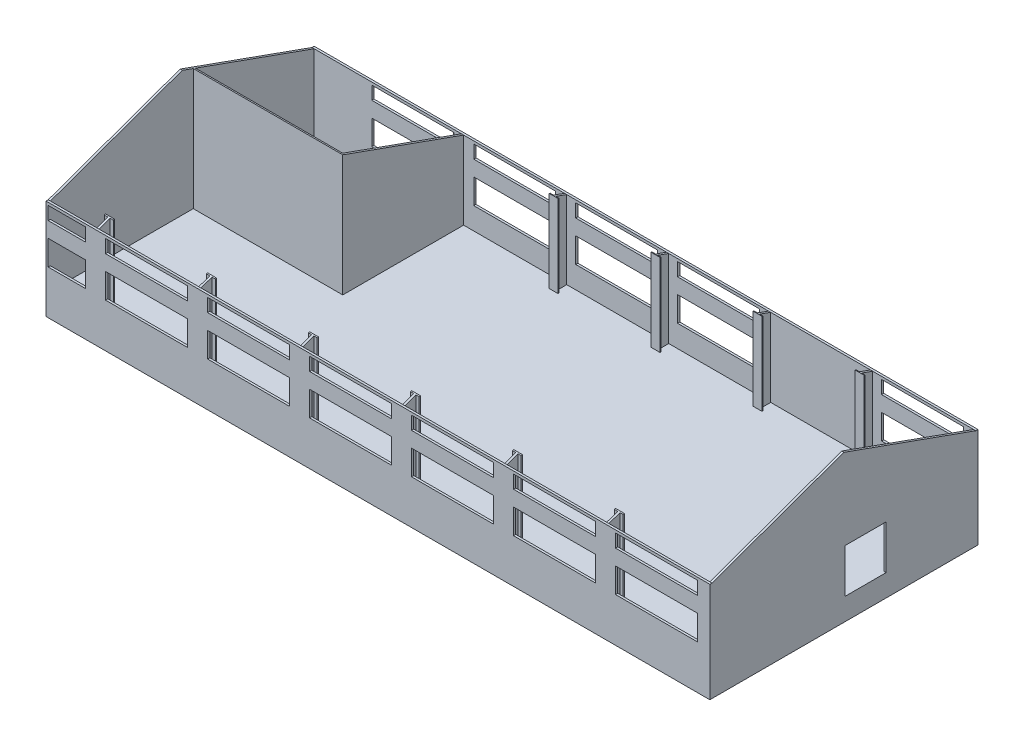
SolidWorks part; units mm, degrees
ref_plane "正面" through (0, 0, 0) normal (0, 0, 1) x (1, 0, 0)
ref_plane "平面" through (0, 0, 0) normal (0, 1, 0) x (1, 0, 0)
ref_plane "右側面" through (0, 0, 0) normal (1, 0, 0) x (0, 0, -1)
sketch "ｽｹｯﾁ3" plane through (0, 0, 0) normal (0, 1, 0) x (1, 0, 0)
  line L1 (-95.6421, 11968.1626) -> (29904.3579, 11968.1626)
  line L2 (-95.6421, 11968.1626) -> (-95.6421, -31.8374)
  line L3 (-95.6421, -31.8374) -> (29904.3579, -31.8374)
  line L4 (29904.3579, 11968.1626) -> (29904.3579, -31.8374)
  dimension "D1" = 30000
  dimension "D2" = 12000
extrude "ﾎﾞｽ - 押し出し2" add sketch "ｽｹｯﾁ3" along normal blind 1000
sketch "ｽｹｯﾁ4" plane through (29904.3579, 0, 0) normal (1, 0, 0) x (0, 0, -1)
  line L0 (-31.8374, 0) -> (-31.8374, 4550)
  line L1 (-31.8374, 4550) -> (5968.1626, 6700)
  line L2 (5968.1626, 6700) -> (11968.1626, 4550)
  line L3 (11968.1626, 4550) -> (11968.1626, 0)
  line L4 (11968.1626, 0) -> (-31.8374, 0)
  dimension "D1" = 12000
  dimension "D2" = 12000
  dimension "D3" = 6000
  dimension "D4" = 4550
  dimension "D5" = 4550
  dimension "D6" = 6700
extrude "ﾎﾞｽ - 押し出し3" add sketch "ｽｹｯﾁ4" along normal blind 100
sketch "ｽｹｯﾁ7" plane through (-95.6421, 0, 0) normal (-1, 0, 0) x (0, 0, 1)
  line L0 (-11968.1626, 0) -> (-11968.1626, 4550)
  line L1 (-11968.1626, 4550) -> (-5968.1626, 6700)
  line L2 (-5968.1626, 6700) -> (31.8374, 4550)
  line L3 (31.8374, 4550) -> (31.8374, 0)
  line L4 (31.8374, 0) -> (-11968.1626, 0)
  dimension "D1" = 6700
  dimension "D2" = 4550
  dimension "D3" = 4550
  dimension "D4" = 6000
  dimension "D5" = 12000
extrude "ﾎﾞｽ - 押し出し4" add sketch "ｽｹｯﾁ7" along normal blind 100
sketch "ｽｹｯﾁ8" plane through (0, 0, -11968.1626) normal (0, 0, -1) x (-1, 0, 0)
  line L1 (-30004.3579, 0) -> (195.6421, 0)
  line L2 (-30004.3579, 0) -> (-30004.3579, 4550)
  line L3 (-30004.3579, 4550) -> (195.6421, 4550)
  line L4 (195.6421, 0) -> (195.6421, 4550)
extrude "ﾎﾞｽ - 押し出し5" add sketch "ｽｹｯﾁ8" along normal blind 100
sketch "ｽｹｯﾁ9" plane through (0, 0, 31.8374) normal (0, 0, 1) x (1, 0, 0)
  line L1 (-195.6421, 0) -> (30004.3579, 0)
  line L2 (-195.6421, 0) -> (-195.6421, 4550)
  line L3 (-195.6421, 4550) -> (30004.3579, 4550)
  line L4 (30004.3579, 0) -> (30004.3579, 4550)
extrude "ﾎﾞｽ - 押し出し7" add sketch "ｽｹｯﾁ9" along normal blind 100
sketch "ｽｹｯﾁ10" plane through (0, 1000, 0) normal (0, 1, 0) x (1, 0, 0)
  line L0 (-95.6421, 6568.1626) -> (6604.3579, 6568.1626)
  line L1 (-95.6421, 11968.1626) -> (-95.6421, -31.8374) construction
  line L2 (6604.3579, 6568.1626) -> (6604.3579, 11968.1626)
  line L3 (29904.3579, 11968.1626) -> (-95.6421, 11968.1626) construction
  line L4 (6604.3579, 11968.1626) -> (6704.3579, 11968.1626)
  line L5 (6704.3579, 11968.1626) -> (6704.3579, 6468.1626)
  line L6 (6704.3579, 6468.1626) -> (-95.6421, 6468.1626)
  line L7 (-95.6421, 6468.1626) -> (-95.6421, 6568.1626)
  dimension "D1" = 5500
  dimension "D2" = 6800
  dimension "D3" = 100
  dimension "D4" = 100
extrude "ﾎﾞｽ - 押し出し8" add sketch "ｽｹｯﾁ10" along normal blind 5700
sketch "ｽｹｯﾁ13" plane through (29904.3579, 0, 0) normal (-1, 0, 0) x (0, 0, 1)
  line L0 (31.8374, 1000) -> (-11968.1626, 1000) construction
  line L1 (-7888.1626, 1000) -> (-6008.1626, 1000)
  line L2 (-7888.1626, 1000) -> (-7888.1626, 3000)
  line L3 (-7888.1626, 3000) -> (-6008.1626, 3000)
  line L4 (-6008.1626, 1000) -> (-6008.1626, 3000)
  dimension "D1" = 1880
  dimension "D2" = 2000
  dimension "D3" = 40
extrude "ｶｯﾄ - 押し出し3" cut sketch "ｽｹｯﾁ13" against normal blind 100
sketch "ｽｹｯﾁ14" plane through (0, 1000, 0) normal (0, 1, 0) x (1, 0, 0)
  line L0 (25314.3579, 11968.1626) -> (25314.3579, 11468.1626)
  line L1 (29904.3579, 11968.1626) -> (6704.3579, 11968.1626) construction
  line L2 (25314.3579, 11468.1626) -> (25464.3579, 11468.1626)
  line L3 (25464.3579, 11468.1626) -> (25464.3579, 11418.1626)
  line L4 (25464.3579, 11418.1626) -> (25064.3579, 11418.1626)
  line L5 (25064.3579, 11418.1626) -> (25064.3579, 11468.1626)
  line L6 (25064.3579, 11468.1626) -> (25214.3579, 11468.1626)
  line L7 (25214.3579, 11468.1626) -> (25214.3579, 11968.1626)
  line L8 (-95.6421, 11968.1626) -> (6604.3579, 11968.1626) construction
  line L9 (25214.3579, 11968.1626) -> (25314.3579, 11968.1626)
  line L10 (25264.3579, 12167.4241) -> (25264.3579, 11163.5533) construction
  line L11 (29904.3579, 11968.1626) -> (29904.3579, 5968.1626) construction
  line L12 (20674.3579, 11968.1626) -> (20674.3579, 11468.1626)
  line L13 (20674.3579, 11468.1626) -> (20824.3579, 11468.1626)
  line L14 (20824.3579, 11468.1626) -> (20824.3579, 11418.1626)
  line L15 (20824.3579, 11418.1626) -> (20424.3579, 11418.1626)
  line L16 (20424.3579, 11418.1626) -> (20424.3579, 11468.1626)
  line L17 (20424.3579, 11468.1626) -> (20574.3579, 11468.1626)
  line L18 (20574.3579, 11468.1626) -> (20574.3579, 11968.1626)
  line L19 (20574.3579, 11968.1626) -> (20674.3579, 11968.1626)
  line L20 (20624.3579, 12167.4241) -> (20624.3579, 11163.5533) construction
  line L21 (16034.3579, 11968.1626) -> (16034.3579, 11468.1626)
  line L22 (16034.3579, 11468.1626) -> (16184.3579, 11468.1626)
  line L23 (16184.3579, 11468.1626) -> (16184.3579, 11418.1626)
  line L24 (16184.3579, 11418.1626) -> (15784.3579, 11418.1626)
  line L25 (15784.3579, 11418.1626) -> (15784.3579, 11468.1626)
  line L26 (15784.3579, 11468.1626) -> (15934.3579, 11468.1626)
  line L27 (15934.3579, 11468.1626) -> (15934.3579, 11968.1626)
  line L28 (15934.3579, 11968.1626) -> (16034.3579, 11968.1626)
  line L29 (15984.3579, 12167.4241) -> (15984.3579, 11163.5533) construction
  line L30 (11394.3579, 11968.1626) -> (11394.3579, 11468.1626)
  line L31 (11394.3579, 11468.1626) -> (11544.3579, 11468.1626)
  line L32 (11544.3579, 11468.1626) -> (11544.3579, 11418.1626)
  line L33 (11544.3579, 11418.1626) -> (11144.3579, 11418.1626)
  line L34 (11144.3579, 11418.1626) -> (11144.3579, 11468.1626)
  line L35 (11144.3579, 11468.1626) -> (11294.3579, 11468.1626)
  line L36 (11294.3579, 11468.1626) -> (11294.3579, 11968.1626)
  line L37 (11294.3579, 11968.1626) -> (11394.3579, 11968.1626)
  line L38 (11344.3579, 12167.4241) -> (11344.3579, 11163.5533) construction
  line L39 (2014.3579, -31.8374) -> (2014.3579, 468.1626)
  line L40 (25214.3579, -31.8374) -> (25214.3579, 468.1626)
  line L41 (2014.3579, 468.1626) -> (1864.3579, 468.1626)
  line L42 (25214.3579, 468.1626) -> (25064.3579, 468.1626)
  line L43 (25064.3579, 468.1626) -> (25064.3579, 518.1626)
  line L44 (25064.3579, 518.1626) -> (25464.3579, 518.1626)
  line L45 (25464.3579, 518.1626) -> (25464.3579, 468.1626)
  line L46 (25464.3579, 468.1626) -> (25314.3579, 468.1626)
  line L47 (25314.3579, 468.1626) -> (25314.3579, -31.8374)
  line L48 (-95.6421, -31.8374) -> (29904.3579, -31.8374) construction
  line L49 (25314.3579, -31.8374) -> (25214.3579, -31.8374)
  line L50 (25264.3579, 648.8294) -> (25264.3579, -317.6522) construction
  line L51 (1864.3579, 468.1626) -> (1864.3579, 518.1626)
  line L52 (1864.3579, 518.1626) -> (2264.3579, 518.1626)
  line L53 (2264.3579, 518.1626) -> (2264.3579, 468.1626)
  line L54 (29904.3579, 5968.1626) -> (29904.3579, -31.8374) construction
  line L55 (20574.3579, -31.8374) -> (20574.3579, 468.1626)
  line L56 (20574.3579, 468.1626) -> (20424.3579, 468.1626)
  line L57 (20424.3579, 468.1626) -> (20424.3579, 518.1626)
  line L58 (20424.3579, 518.1626) -> (20824.3579, 518.1626)
  line L59 (20824.3579, 518.1626) -> (20824.3579, 468.1626)
  line L60 (20824.3579, 468.1626) -> (20674.3579, 468.1626)
  line L61 (20674.3579, 468.1626) -> (20674.3579, -31.8374)
  line L62 (20674.3579, -31.8374) -> (20574.3579, -31.8374)
  line L63 (20624.3579, 648.8294) -> (20624.3579, -317.6522) construction
  line L64 (15934.3579, -31.8374) -> (15934.3579, 468.1626)
  line L65 (15934.3579, 468.1626) -> (15784.3579, 468.1626)
  line L66 (15784.3579, 468.1626) -> (15784.3579, 518.1626)
  line L67 (15784.3579, 518.1626) -> (16184.3579, 518.1626)
  line L68 (16184.3579, 518.1626) -> (16184.3579, 468.1626)
  line L69 (16184.3579, 468.1626) -> (16034.3579, 468.1626)
  line L70 (16034.3579, 468.1626) -> (16034.3579, -31.8374)
  line L71 (16034.3579, -31.8374) -> (15934.3579, -31.8374)
  line L72 (15984.3579, 648.8294) -> (15984.3579, -317.6522) construction
  line L73 (11294.3579, -31.8374) -> (11294.3579, 468.1626)
  line L74 (11294.3579, 468.1626) -> (11144.3579, 468.1626)
  line L75 (11144.3579, 468.1626) -> (11144.3579, 518.1626)
  line L76 (11144.3579, 518.1626) -> (11544.3579, 518.1626)
  line L77 (11544.3579, 518.1626) -> (11544.3579, 468.1626)
  line L78 (11544.3579, 468.1626) -> (11394.3579, 468.1626)
  line L79 (11394.3579, 468.1626) -> (11394.3579, -31.8374)
  line L80 (11394.3579, -31.8374) -> (11294.3579, -31.8374)
  line L81 (11344.3579, 648.8294) -> (11344.3579, -317.6522) construction
  line L82 (6654.3579, -31.8374) -> (6654.3579, 468.1626)
  line L83 (6654.3579, 468.1626) -> (6504.3579, 468.1626)
  line L84 (6504.3579, 468.1626) -> (6504.3579, 518.1626)
  line L85 (6504.3579, 518.1626) -> (6904.3579, 518.1626)
  line L86 (6904.3579, 518.1626) -> (6904.3579, 468.1626)
  line L87 (6904.3579, 468.1626) -> (6754.3579, 468.1626)
  line L88 (6754.3579, 468.1626) -> (6754.3579, -31.8374)
  line L89 (6754.3579, -31.8374) -> (6654.3579, -31.8374)
  line L90 (6704.3579, 648.8294) -> (6704.3579, -317.6522) construction
  line L91 (29904.3579, -31.8374) -> (-95.6421, -31.8374) construction
  line L92 (2264.3579, 468.1626) -> (2114.3579, 468.1626)
  line L93 (2114.3579, 468.1626) -> (2114.3579, -31.8374)
  line L94 (2114.3579, -31.8374) -> (2014.3579, -31.8374)
  line L95 (2064.3579, 648.8294) -> (2064.3579, -317.6522) construction
  dimension "D1" = 100
  dimension "D2" = 50
  dimension "D3" = 400
  dimension "D4" = 150
  dimension "D5" = 50
  dimension "D6" = 4640
  dimension "D7" = 500
  dimension "D8" = 100
  dimension "D9" = 50
  dimension "D10" = 400
  dimension "D11" = 150
  dimension "D12" = 50
  dimension "D13" = 500
  dimension "D14" = 100
  dimension "D15" = 50
  dimension "D16" = 400
  dimension "D17" = 150
  dimension "D18" = 50
  dimension "D19" = 500
  dimension "D20" = 100
  dimension "D21" = 50
  dimension "D22" = 400
  dimension "D23" = 150
  dimension "D24" = 50
  dimension "D25" = 500
  dimension "D26" = 4640
  dimension "D27" = 4640
  dimension "D28" = 4640
  dimension "D29" = 100
  dimension "D30" = 50
  dimension "D31" = 400
  dimension "D32" = 150
  dimension "D33" = 500
  dimension "D34" = 50
  dimension "D35" = 4640
  dimension "D36" = 100
  dimension "D37" = 50
  dimension "D38" = 400
  dimension "D39" = 150
  dimension "D40" = 50
  dimension "D41" = 100
  dimension "D42" = 50
  dimension "D43" = 400
  dimension "D44" = 150
  dimension "D45" = 50
  dimension "D46" = 100
  dimension "D47" = 50
  dimension "D48" = 400
  dimension "D49" = 150
  dimension "D50" = 50
  dimension "D51" = 100
  dimension "D52" = 50
  dimension "D53" = 400
  dimension "D54" = 150
  dimension "D55" = 50
  dimension "D56" = 500
  dimension "D57" = 500
  dimension "D58" = 500
  dimension "D59" = 500
  dimension "D60" = 4640
  dimension "D61" = 4640
  dimension "D62" = 4640
  dimension "D63" = 4640
  dimension "D64" = 100
  dimension "D65" = 50
  dimension "D66" = 400
  dimension "D67" = 50
  dimension "D68" = 500
  dimension "D69" = 4640
  dimension "D70" = 150
extrude "ﾎﾞｽ - 押し出し9" add sketch "ｽｹｯﾁ14" along normal blind 4000
sketch "ｽｹｯﾁ15" plane through (0, 0, -11968.1626) normal (0, 0, 1) x (1, 0, 0)
  line L0 (29904.3579, 1000) -> (25314.3579, 1000) construction
  line L1 (25714.3579, 3130) -> (29444.3579, 3130)
  line L2 (25714.3579, 3130) -> (25714.3579, 2000)
  line L3 (25714.3579, 2000) -> (29444.3579, 2000)
  line L4 (29444.3579, 3130) -> (29444.3579, 2000)
  line L5 (25714.3579, 4430) -> (29444.3579, 4430)
  line L6 (25714.3579, 4430) -> (25714.3579, 3830)
  line L7 (25714.3579, 3830) -> (29444.3579, 3830)
  line L8 (29444.3579, 4430) -> (29444.3579, 3830)
  line L9 (25314.3579, 4550) -> (25314.3579, 1000) construction
  line L10 (11294.3579, 4550) -> (11294.3579, 1000) construction
  line L11 (11294.3579, 1000) -> (6704.3579, 1000) construction
  line L18 (16439.3579, 3130) -> (20169.3579, 3130)
  line L19 (16439.3579, 2000) -> (20169.3579, 2000)
  line L20 (20169.3579, 3130) -> (20169.3579, 2000)
  line L21 (16439.3579, 3130) -> (16439.3579, 2000)
  line L22 (16439.3579, 4430) -> (16439.3579, 3830)
  line L23 (16439.3579, 3830) -> (20169.3579, 3830)
  line L24 (16439.3579, 4430) -> (20169.3579, 4430)
  line L25 (20169.3579, 4430) -> (20169.3579, 3830)
  line L26 (11801.8579, 3130) -> (15531.8579, 3130)
  line L27 (11801.8579, 2000) -> (15531.8579, 2000)
  line L28 (15531.8579, 3130) -> (15531.8579, 2000)
  line L29 (11801.8579, 3130) -> (11801.8579, 2000)
  line L30 (11801.8579, 4430) -> (11801.8579, 3830)
  line L31 (11801.8579, 3830) -> (15531.8579, 3830)
  line L32 (11801.8579, 4430) -> (15531.8579, 4430)
  line L33 (15531.8579, 4430) -> (15531.8579, 3830)
  line L34 (7164.3579, 3130) -> (10894.3579, 3130)
  line L35 (7164.3579, 2000) -> (10894.3579, 2000)
  line L36 (10894.3579, 3130) -> (10894.3579, 2000)
  line L37 (7164.3579, 3130) -> (7164.3579, 2000)
  line L38 (7164.3579, 4430) -> (7164.3579, 3830)
  line L39 (7164.3579, 3830) -> (10894.3579, 3830)
  line L40 (7164.3579, 4430) -> (10894.3579, 4430)
  line L41 (10894.3579, 4430) -> (10894.3579, 3830)
  line L42 (21076.8579, 3130) -> (24806.8579, 3130) [skipped]
  line L43 (21076.8579, 2000) -> (24806.8579, 2000) [skipped]
  line L44 (24806.8579, 3130) -> (24806.8579, 2000) [skipped]
  line L45 (21076.8579, 3130) -> (21076.8579, 2000) [skipped]
  line L46 (21076.8579, 4430) -> (21076.8579, 3830) [skipped]
  line L47 (21076.8579, 3830) -> (24806.8579, 3830) [skipped]
  line L48 (21076.8579, 4430) -> (24806.8579, 4430) [skipped]
  line L49 (24806.8579, 4430) -> (24806.8579, 3830) [skipped]
  line L52 (6254.3579, 3130) -> (6254.3579, 2000)
  line L53 (2524.3579, 3130) -> (2524.3579, 2000)
  line L54 (2524.3579, 2000) -> (6254.3579, 2000)
  line L55 (2524.3579, 3130) -> (6254.3579, 3130)
  line L56 (2524.3579, 3830) -> (6254.3579, 3830)
  line L57 (2524.3579, 4430) -> (2524.3579, 3830)
  line L58 (2524.3579, 4430) -> (6254.3579, 4430)
  line L59 (6254.3579, 4430) -> (6254.3579, 3830)
  dimension "D1" = 1000
  dimension "D2" = 3730
  dimension "D3" = 400
  dimension "D4" = 700
  dimension "D5" = 3730
  dimension "D6" = 400
  dimension "D7" = 1130
  dimension "D8" = 600
  dimension "D10" = 3730
  dimension "D11" = 400
  dimension "D12" = 1000
  dimension "D9" = 5
extrude "ｶｯﾄ - 押し出し4" cut sketch "ｽｹｯﾁ15" against normal blind 100
sketch "ｽｹｯﾁ16" plane through (0, 0, 31.8374) normal (0, 0, -1) x (-1, 0, 0)
  line L0 (-25314.3579, 1000) -> (-29904.3579, 1000) construction
  line L1 (-29444.3579, 3130) -> (-25714.3579, 3130)
  line L2 (-29444.3579, 3130) -> (-29444.3579, 2000)
  line L3 (-29444.3579, 2000) -> (-25714.3579, 2000)
  line L4 (-25714.3579, 3130) -> (-25714.3579, 2000)
  line L5 (-29444.3579, 4430) -> (-25714.3579, 4430)
  line L6 (-29444.3579, 4430) -> (-29444.3579, 3830)
  line L7 (-29444.3579, 3830) -> (-25714.3579, 3830)
  line L8 (-25714.3579, 4430) -> (-25714.3579, 3830)
  line L9 (-25314.3579, 4550) -> (-25314.3579, 1000) construction
  line L10 (-24804.3579, 3130) -> (-21074.3579, 3130)
  line L11 (-24804.3579, 2000) -> (-21074.3579, 2000)
  line L12 (-24804.3579, 3130) -> (-24804.3579, 2000)
  line L13 (-21074.3579, 3130) -> (-21074.3579, 2000)
  line L14 (-24804.3579, 3830) -> (-21074.3579, 3830)
  line L15 (-24804.3579, 4430) -> (-24804.3579, 3830)
  line L16 (-24804.3579, 4430) -> (-21074.3579, 4430)
  line L17 (-21074.3579, 4430) -> (-21074.3579, 3830)
  line L18 (-20164.3579, 3130) -> (-16434.3579, 3130)
  line L19 (-20164.3579, 2000) -> (-16434.3579, 2000)
  line L20 (-20164.3579, 3130) -> (-20164.3579, 2000)
  line L21 (-16434.3579, 3130) -> (-16434.3579, 2000)
  line L22 (-20164.3579, 3830) -> (-16434.3579, 3830)
  line L23 (-20164.3579, 4430) -> (-20164.3579, 3830)
  line L24 (-20164.3579, 4430) -> (-16434.3579, 4430)
  line L25 (-16434.3579, 4430) -> (-16434.3579, 3830)
  line L26 (-15524.3579, 3130) -> (-11794.3579, 3130)
  line L27 (-15524.3579, 2000) -> (-11794.3579, 2000)
  line L28 (-15524.3579, 3130) -> (-15524.3579, 2000)
  line L29 (-11794.3579, 3130) -> (-11794.3579, 2000)
  line L30 (-15524.3579, 3830) -> (-11794.3579, 3830)
  line L31 (-15524.3579, 4430) -> (-15524.3579, 3830)
  line L32 (-15524.3579, 4430) -> (-11794.3579, 4430)
  line L33 (-11794.3579, 4430) -> (-11794.3579, 3830)
  line L34 (-10884.3579, 3130) -> (-7154.3579, 3130)
  line L35 (-10884.3579, 2000) -> (-7154.3579, 2000)
  line L36 (-10884.3579, 3130) -> (-10884.3579, 2000)
  line L37 (-7154.3579, 3130) -> (-7154.3579, 2000)
  line L38 (-10884.3579, 3830) -> (-7154.3579, 3830)
  line L39 (-10884.3579, 4430) -> (-10884.3579, 3830)
  line L40 (-10884.3579, 4430) -> (-7154.3579, 4430)
  line L41 (-7154.3579, 4430) -> (-7154.3579, 3830)
  line L42 (-6244.3579, 3130) -> (-2514.3579, 3130)
  line L43 (-6244.3579, 2000) -> (-2514.3579, 2000)
  line L44 (-6244.3579, 3130) -> (-6244.3579, 2000)
  line L45 (-2514.3579, 3130) -> (-2514.3579, 2000)
  line L46 (-6244.3579, 3830) -> (-2514.3579, 3830)
  line L47 (-6244.3579, 4430) -> (-6244.3579, 3830)
  line L48 (-6244.3579, 4430) -> (-2514.3579, 4430)
  line L49 (-2514.3579, 4430) -> (-2514.3579, 3830)
  line L50 (-1604.3579, 3130) -> (95.6421, 3130)
  line L51 (-1604.3579, 2000) -> (95.6421, 2000)
  line L52 (-1604.3579, 3130) -> (-1604.3579, 2000)
  line L53 (-2114.3579, 4550) -> (-2114.3579, 1000) construction
  line L54 (-1604.3579, 3830) -> (95.6421, 3830)
  line L55 (-1604.3579, 4430) -> (-1604.3579, 3830)
  line L56 (-1604.3579, 4430) -> (95.6421, 4430)
  line L57 (95.6421, 1000) -> (-2014.3579, 1000) construction
  line L58 (95.6421, 4430) -> (95.6421, 3830)
  line L59 (95.6421, 1000) -> (95.6421, 4550) construction
  line L60 (95.6421, 3130) -> (95.6421, 2000)
  line L62 (2125.6421, 4430) -> (2125.6421, 3830) [skipped]
  line L63 (2125.6421, 3130) -> (2125.6421, 2000) [skipped]
  dimension "D1" = 3730
  dimension "D2" = 3730
  dimension "D3" = 700
  dimension "D4" = 600
  dimension "D5" = 1000
  dimension "D6" = 1130
  dimension "D7" = 400
  dimension "D8" = 400
  dimension "D10" = 400
  dimension "D11" = 1000
  dimension "D9" = 7
extrude "ｶｯﾄ - 押し出し5" cut sketch "ｽｹｯﾁ16" against normal blind 100
sketch "ｽｹｯﾁ12" plane through (-95.6421, 0, 0) normal (-1, 0, 0) x (0, 0, 1)
  line L0 (-6468.1626, 6520.8333) -> (-11968.1626, 4550)
  line L1 (-11968.1626, 4550) -> (-11968.1626, 6700)
  line L2 (-11968.1626, 6700) -> (-6468.1626, 6700)
  line L3 (-6468.1626, 6700) -> (-6468.1626, 6520.8333)
  line L4 (-5968.1626, 6700) -> (31.8374, 6700)
  line L7 (31.8374, 4550) -> (31.8374, 6700)
  line L8 (31.8374, 4550) -> (-5968.1626, 6700)
  dimension "D1" = 6000
extrude "ｶｯﾄ - 押し出し2" cut sketch "ｽｹｯﾁ12" against normal through all
